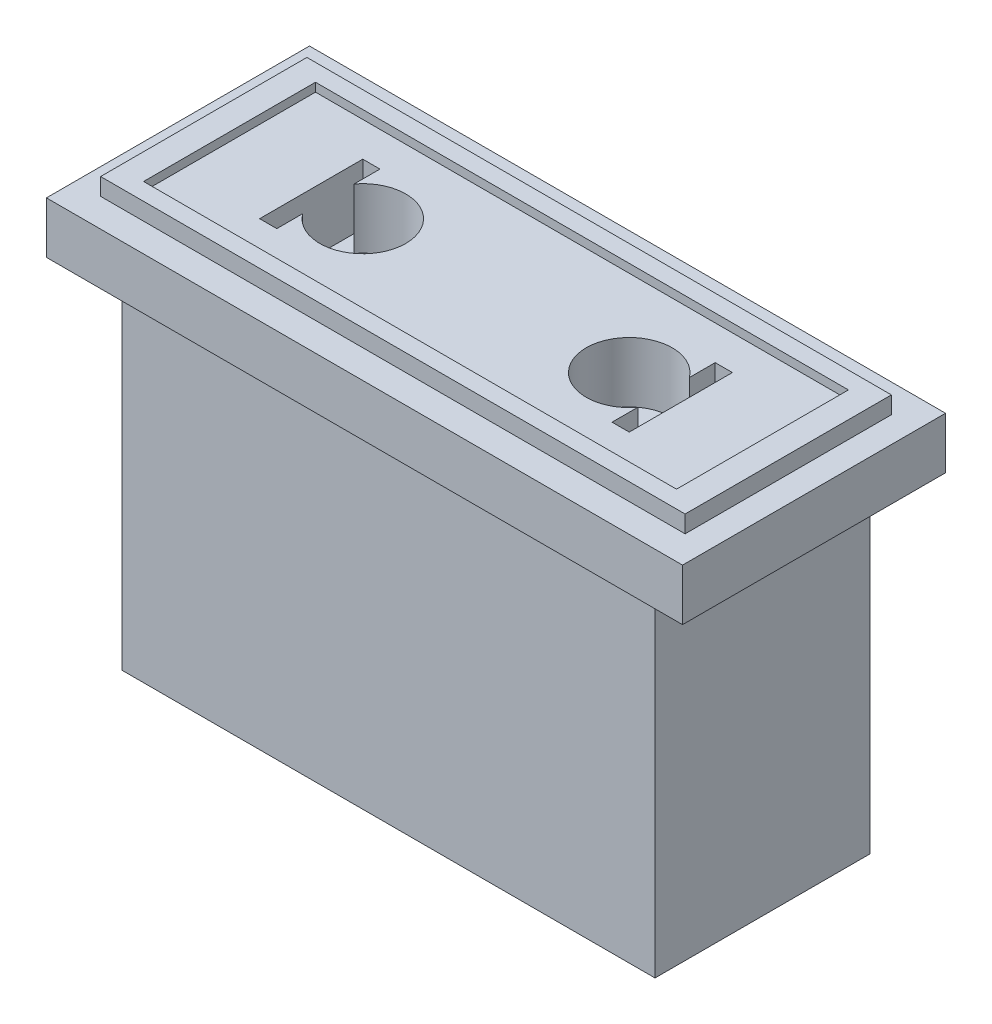
SolidWorks part; units mm, degrees
ref_plane "Front Plane" through (0, 0, 0) normal (0, 0, 1) x (1, 0, 0)
ref_plane "Top Plane" through (0, 0, 0) normal (0, 1, 0) x (1, 0, 0)
ref_plane "Right Plane" through (0, 0, 0) normal (1, 0, 0) x (0, 0, -1)
sketch "Sketch1" plane through (0, 0, 0) normal (0, 1, 0) x (1, 0, 0)
  line L1 (18.5, -7.65) -> (-18.5, -7.65)
  line L2 (18.5, -7.65) -> (18.5, 7.65)
  line L3 (18.5, 7.65) -> (-18.5, 7.65)
  line L4 (-18.5, -7.65) -> (-18.5, 7.65)
  line L5 (18.5, -7.65) -> (-18.5, 7.65) construction
  line L6 (18.5, 7.65) -> (-18.5, -7.65) construction
  point P0 (0, 0)
  dimension "D1" = 37
  dimension "D2" = 15.3
extrude "Boss-Extrude1" add sketch "Sketch1" along normal blind 3
sketch "Sketch2" plane through (0, 3, 0) normal (0, 1, 0) x (1, 0, 0)
  line L1 (17, -6) -> (-17, -6)
  line L2 (17, -6) -> (17, 6)
  line L3 (17, 6) -> (-17, 6)
  line L4 (-17, -6) -> (-17, 6)
  line L5 (17, -6) -> (-17, 6) construction
  line L6 (17, 6) -> (-17, -6) construction
  point P0 (0, 0)
  dimension "D1" = 34
  dimension "D2" = 12
extrude "Boss-Extrude2" add sketch "Sketch2" along normal blind 1
sketch "Sketch3" plane through (0, 4, 0) normal (0, 1, 0) x (1, 0, 0)
  line L1 (15.5, -5) -> (-15.5, -5)
  line L2 (15.5, -5) -> (15.5, 5)
  line L3 (15.5, 5) -> (-15.5, 5)
  line L4 (-15.5, -5) -> (-15.5, 5)
  line L5 (15.5, -5) -> (-15.5, 5) construction
  line L6 (15.5, 5) -> (-15.5, -5) construction
  point P0 (0, 0)
  dimension "D1" = 31
  dimension "D2" = 10
extrude "Cut-Extrude1" cut sketch "Sketch3" against normal blind 0.5
sketch "Sketch4" plane through (0, 3.5, 0) normal (0, 1, 0) x (1, 0, 0)
  line L0 (0, 5) -> (0, -5) construction
  line L1 (15.5, 5) -> (-15.5, 5) construction
  line L2 (-15.5, -5) -> (15.5, -5) construction
  line L3 (-15.5, 0) -> (0, 0) construction
  line L4 (-10.75, 3) -> (-9.75, 3)
  line L5 (-10.75, 3) -> (-10.75, -3)
  line L6 (-10.75, -3) -> (-9.75, -3)
  line L7 (-9.75, 3) -> (-9.75, 1.5)
  line L8 (-10.75, 3) -> (-9.75, -3) construction
  line L9 (-10.75, -3) -> (-9.75, 3) construction
  line L10 (-15.5, 5) -> (-15.5, -5) construction
  line L11 (-9.75, -1.5) -> (-9.75, -3)
  line L12 (9.75, -1.5) -> (9.75, -3)
  line L13 (10.75, -3) -> (9.75, -3)
  line L14 (10.75, 3) -> (10.75, -3)
  line L15 (9.75, 3) -> (9.75, 1.5)
  line L16 (10.75, 3) -> (9.75, 3)
  arc A1 (-9.75, -1.5) -> (-9.75, 1.5) centre (-7.75, 0) ccw
  arc A2 (9.75, -1.5) -> (9.75, 1.5) centre (7.75, 0) cw
  point P6 (-10.25, 0)
  point P16 (-7.75, 0)
  dimension "D3" = 2.5
  dimension "D4" = 2.5
  dimension "D1" = 1
  dimension "D2" = 6
extrude "Cut-Extrude2" cut sketch "Sketch4" against normal blind 5
sketch "Sketch5" plane through (0, 0, 0) normal (0, -1, 0) x (1, 0, 0)
  line L1 (15.5, -6.25) -> (-15.5, -6.25)
  line L2 (15.5, -6.25) -> (15.5, 6.25)
  line L3 (15.5, 6.25) -> (-15.5, 6.25)
  line L4 (-15.5, -6.25) -> (-15.5, 6.25)
  line L5 (15.5, -6.25) -> (-15.5, 6.25) construction
  line L6 (15.5, 6.25) -> (-15.5, -6.25) construction
  point P0 (0, 0)
  dimension "D1" = 31
  dimension "D2" = 12.5
extrude "Boss-Extrude3" add sketch "Sketch5" along normal blind 20
